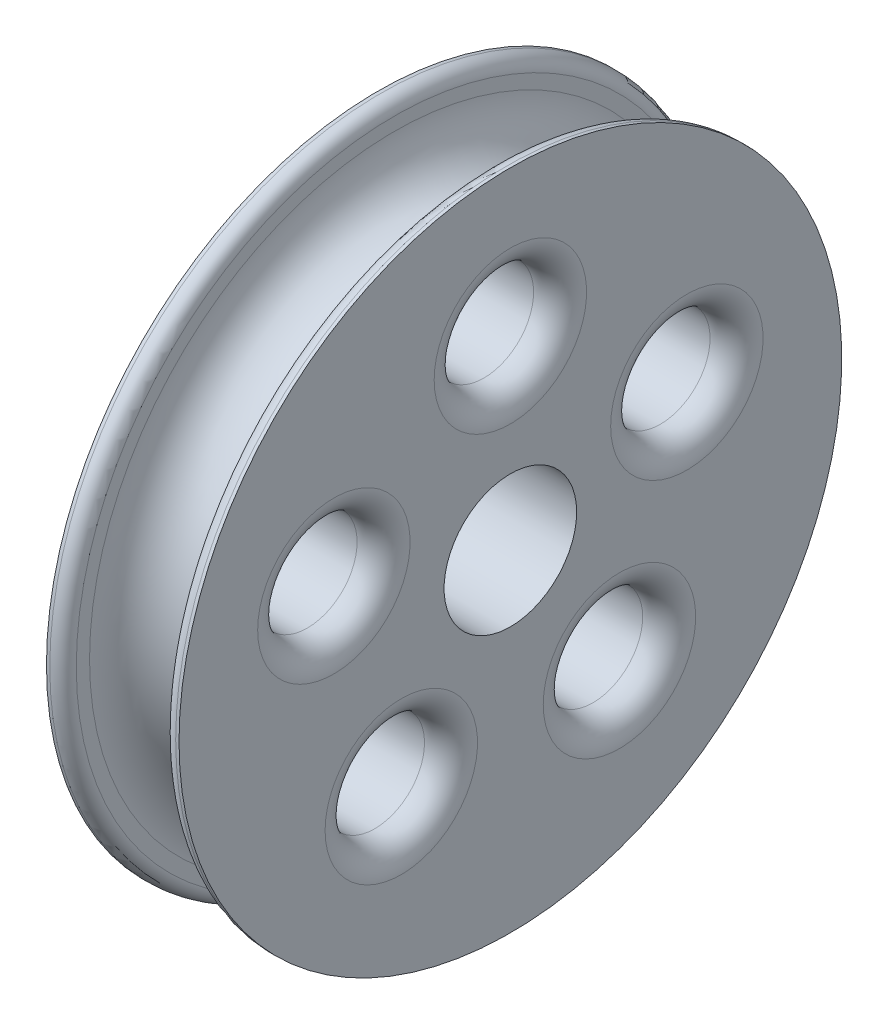
SolidWorks part; units mm, degrees
ref_plane "Front Plane" through (0, 0, 0) normal (0, 0, 1) x (1, 0, 0)
ref_plane "Top Plane" through (0, 0, 0) normal (0, 1, 0) x (1, 0, 0)
ref_plane "Right Plane" through (0, 0, 0) normal (1, 0, 0) x (0, 0, -1)
sketch "Sketch2" plane through (0, 0, 0) normal (0, 0, 1) x (1, 0, 0)
  line L0 (0, 93.1007) -> (0, -30.721) construction
  line L1 (-12.7, 0) -> (12.7, 0)
  line L2 (-12.7, 0) -> (-12.7, 63.5)
  line L3 (-12.7, 63.5) -> (-9.525, 63.5)
  line L4 (12.7, 0) -> (12.7, 63.5)
  line L5 (-9.525, 58.42) -> (-9.525, 63.5)
  line L6 (9.525, 58.42) -> (9.525, 63.5)
  line L7 (9.525, 63.5) -> (12.7, 63.5)
  arc A0 (-9.525, 58.42) -> (9.525, 58.42) centre (0, 58.42) ccw
  point P4 (0, 0)
  dimension "D3" = 19.05
  dimension "D1" = 25.4
  dimension "D2" = 63.5
  dimension "D4" = 5.08
revolve "Revolve3" add sketch "Sketch2" angle 360 about L1
sketch "Sketch3" plane through (12.7, 0, 0) normal (1, 0, 0) x (0, 0, -1)
  line L0 (0, 72.3447) -> (0, -71.7534) construction
  circle A0 centre (0, 35.56) radius 9.525
  circle A1 centre (33.8196, 10.9886) radius 9.525
  circle A2 centre (20.9016, -28.7686) radius 9.525
  circle A3 centre (-20.9016, -28.7686) radius 9.525
  circle A4 centre (-33.8196, 10.9886) radius 9.525
  dimension "D1" = 19.05
  dimension "D2" = 35.56
  dimension "D3" = 5
extrude "Cut-Extrude2" cut sketch "Sketch3" against normal through all
fillet "Fillet3" radius 5.08 10 edges at (12.7, 10.9886, 24.2946) (-12.7, 10.9886, 24.2946) (12.7, -28.7686, 11.3766) (-12.7, -28.7686, 11.3766) (12.7, -28.7686, -30.4266) (-12.7, -28.7686, -30.4266) (12.7, 10.9886, -43.3446) (-12.7, 10.9886, -43.3446) (12.7, 35.56, -9.525) (-12.7, 35.56, -9.525)
fillet "Fillet4" radius 2.54 2 edges at (9.525, 0, 63.5) (-9.525, 0, 63.5)
sketch "Sketch4" plane through (12.7, 0, 0) normal (1, 0, 0) x (0, 0, -1)
  circle A0 centre (0, 0) radius 12.7
  dimension "D1" = 25.4
extrude "Cut-Extrude3" cut sketch "Sketch4" against normal through all
